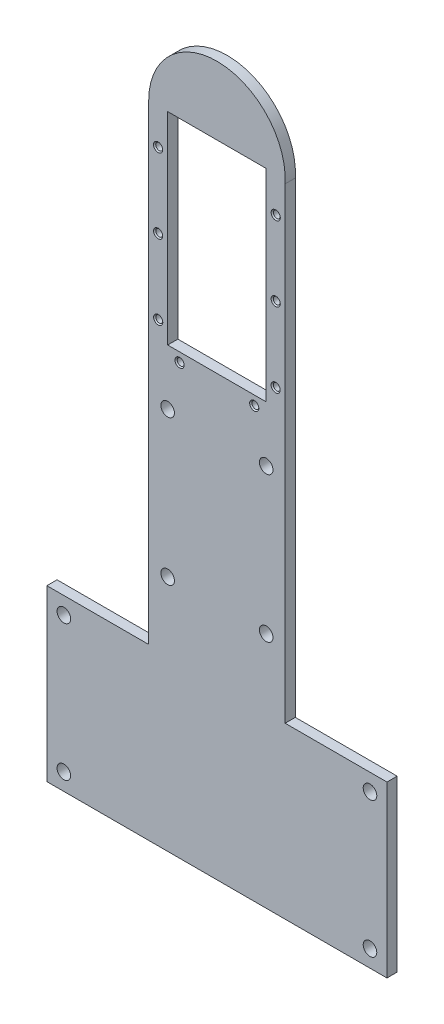
SolidWorks part; units mm, degrees
ref_plane "Plano frontal" through (0, 0, 0) normal (0, 0, 1) x (1, 0, 0)
ref_plane "Plano superior" through (0, 0, 0) normal (0, 1, 0) x (1, 0, 0)
ref_plane "Plano direito" through (0, 0, 0) normal (1, 0, 0) x (0, 0, -1)
sketch "Esboço1" plane through (0, 0, 0) normal (0, 0, 1) x (1, 0, 0)
  line L0 (-20.1038, 0.7539) -> (-20.1038, -138)
  line L2 (20.0962, -138) -> (20.0962, -0.3909)
  line L3 (-20.1038, -138) -> (-50.1038, -138)
  line L4 (-50.1038, -138) -> (-50.1038, -188)
  line L5 (-50.1038, -188) -> (50.0962, -188)
  line L6 (50.0962, -188) -> (50.0962, -138)
  line L7 (50.0962, -138) -> (20.0962, -138)
  line L8 (0, 14) -> (0, -219.3382) construction
  line L9 (-14.5, 0.7539) -> (-14.5, -58.7961)
  line L10 (-14.5, -58.7961) -> (14.525, -58.7961)
  line L11 (14.525, -58.7961) -> (14.525, 0.7539)
  line L12 (14.525, 0.7539) -> (-14.5, 0.7539)
  line L13 (-14.5, 0.7539) -> (14.525, 0.7539)
  line L14 (-20.0875, 20.8702) -> (20.1125, 20.8702) construction
  circle A1 centre (45.0962, -143) radius 2
  circle A3 centre (45.0962, -183) radius 2
  circle A4 centre (-45.0962, -183) radius 2
  circle A5 centre (-45.0962, -143) radius 2
  arc A6 (20.0962, -0.3909) -> (-20.1038, 0.7539) centre (0.0125, 0.7539) ccw
  circle A7 centre (14.5162, -75.1694) radius 2
  circle A8 centre (14.5162, -117.954) radius 2
  circle A9 centre (-14.5162, -117.954) radius 2
  circle A10 centre (-14.5162, -75.1694) radius 2
  circle A11 centre (17.325, -9.7461) radius 1.025
  circle A12 centre (-17.325, -9.7461) radius 1.025
  circle A13 centre (17.3125, -31.7461) radius 1.025
  circle A14 centre (17.3, -53.7461) radius 1.025
  circle A15 centre (-17.3, -53.7461) radius 1.025
  circle A16 centre (-17.3125, -31.7461) radius 1.025
  circle A17 centre (11, -61.5461) radius 1.025
  circle A18 centre (-11, -61.5461) radius 1.025
  point P48 (0, 0)
  point P49 (0, 0)
  point P50 (0, 0)
  point P51 (0, 0)
  point P54 (0, 0)
  dimension "D1" = 5
  dimension "D5" = 30
  dimension "D6" = 30
  dimension "D7" = 50
  dimension "D8" = 5
  dimension "D9" = 4
  dimension "D10" = 4
  dimension "D13" = 5.58
  dimension "D15" = 10.5
  dimension "D20" = 2.8
  dimension "D2" = 5
  dimension "D3" = 40.2
  dimension "D4" = 20.1
  dimension "D11" = 14.525
  dimension "D12" = 59.55
  dimension "D14" = 5.58
  dimension "D16" = 22
  dimension "D17" = 22
  dimension "D18" = 7.8
  dimension "D19" = 6.3
  dimension "D21" = 22
  dimension "D22" = 2.8
extrude "Ressalto-extrusão2" add sketch "Esboço1" along normal blind 3 contours L2 A6 L0 L3 L4 L5 L6 L7 A9 A8 A7 A5 L12 L11 L10 L9 A1 A3 A4 A10
chamfer "Chanfro1" distance 0.325 angle 45 8 edges at (-16.3, -9.7461, 3) (-16.2875, -31.7461, 3) (-16.275, -53.7461, 3) (-9.975, -61.5461, 3) (12.025, -61.5461, 3) (18.325, -53.7461, 3) (18.3375, -31.7461, 3) (18.35, -9.7461, 3)
